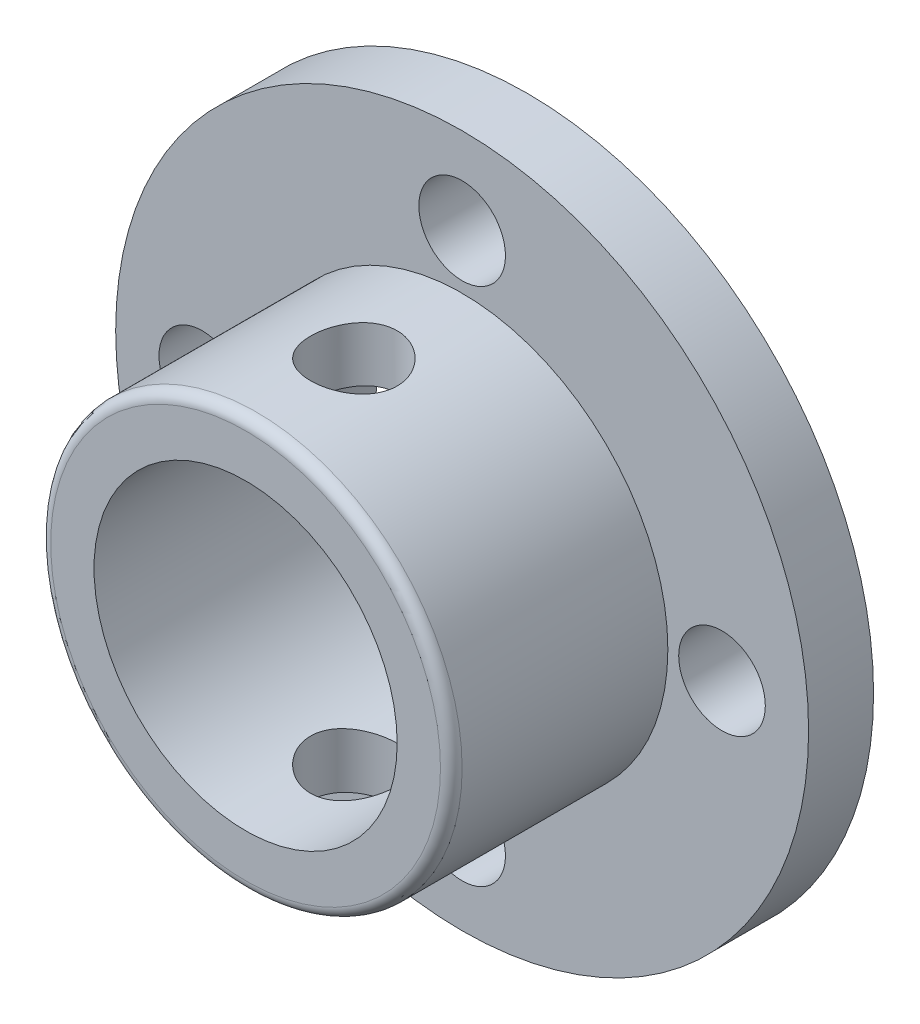
SolidWorks part; units mm, degrees
ref_plane "Front Plane" through (0, 0, 0) normal (0, 0, 1) x (1, 0, 0)
ref_plane "Top Plane" through (0, 0, 0) normal (0, 1, 0) x (1, 0, 0)
ref_plane "Right Plane" through (0, 0, 0) normal (1, 0, 0) x (0, 0, -1)
sketch "Sketch5" plane through (0, 0, 0) normal (0, 0, 1) x (1, 0, 0)
  circle A0 centre (0, 0) radius 16
  dimension "D1" = 32
extrude "Boss-Extrude3" add sketch "Sketch5" along normal blind 3
sketch "Sketch6" plane through (0, 0, 3) normal (0, 0, 1) x (1, 0, 0)
  circle A0 centre (0, 0) radius 9.5
  dimension "D1" = 19
extrude "Boss-Extrude4" add sketch "Sketch6" along normal blind 10
sketch "Sketch7" plane through (0, 0, 13) normal (0, 0, 1) x (1, 0, 0)
  circle A0 centre (0, 0) radius 7
  dimension "D1" = 14
extrude "Cut-Extrude1" cut sketch "Sketch7" against normal through all
sketch "Sketch8" plane through (0, 0, 0) normal (0, 0, -1) x (-1, 0, 0)
  circle A0 centre (12, 0) radius 2
  circle A1 centre (0, -12) radius 2
  circle A2 centre (-12, 0) radius 2
  circle A3 centre (0, 12) radius 2
  point P12 (0, 0)
  dimension "D1" = 4
  dimension "D2" = 12
  dimension "D3" = 4
extrude "Cut-Extrude2" cut sketch "Sketch8" against normal through all
sketch "Sketch9" plane through (0, 0, 0) normal (0, 1, 0) x (1, 0, 0)
  line L0 (-9.5, -13) -> (9.5, -13) construction
  circle A0 centre (0, -8) radius 2
  dimension "D1" = 4
  dimension "D2" = 5
extrude "Cut-Extrude4" cut sketch "Sketch9" against normal through all both and the other way through all
sketch "Sketch10" plane through (0, 0, 0) normal (0, 0, -1) x (-1, 0, 0)
  line L0 (-12, 0) -> (12, 0) construction
  line L1 (0, 12) -> (0, -12) construction
  line L2 (-12, 0) -> (0, 12) construction
  line L3 (-12, 0) -> (0, -12) construction
fillet "Fillet1" radius 0.5 1 edges at (9.5, 0, 13)
